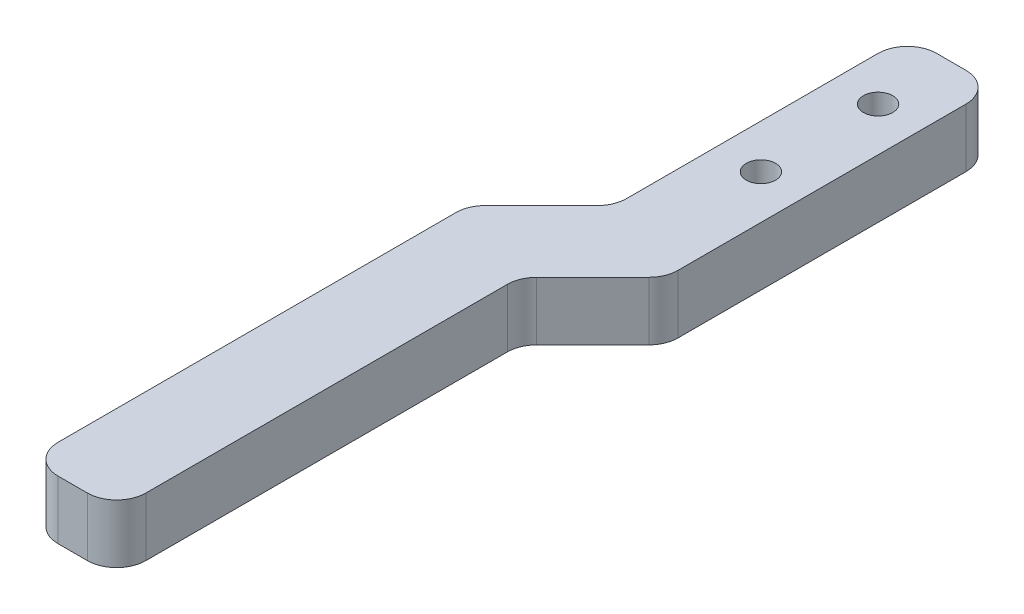
SolidWorks part; units mm, degrees
material "Thornel Mat VMA"
ref_plane "前视基准面" through (0, 0, 0) normal (0, 0, 1) x (1, 0, 0)
ref_plane "上视基准面" through (0, 0, 0) normal (0, 1, 0) x (1, 0, 0)
ref_plane "右视基准面" through (0, 0, 0) normal (1, 0, 0) x (0, 0, -1)
other "Configuration Table"
sketch "草图1" plane through (0, 0, 0) normal (0, 1, 0) x (1, 0, 0)
  line L0 (0, 0) -> (0, 40.389) construction
  line L1 (0, 0) -> (49.8304, 0) construction
  line L2 (0, 35) -> (25, 35) construction
  line L3 (25, 35) -> (25, 30) construction
  line L5 (25, 30) -> (15, 20) construction
  line L6 (25, -30) -> (15, -20) construction
  line L7 (25, 30) -> (25, 40)
  line L8 (25, -35) -> (25, -30) construction
  line L9 (0, -35) -> (25, -35) construction
  line L10 (0, 35) -> (0, -35) construction
  line L12 (31, 25.5147) -> (31, 37.5147)
  line L14 (25, 40) -> (30, 45)
  line L17 (31, 37.5147) -> (36, 42.5147)
  line L18 (30, 45) -> (30, 65)
  line L19 (30, 65) -> (36, 65)
  line L20 (36, 65) -> (36, 42.5147)
  line L21 (33, 65) -> (33, 39.979) construction
  line L22 (0, 0) -> (25, 0) construction
  line L23 (25, 0) -> (25, 30) construction
  line L24 (25, 30) -> (25, 10)
  line L25 (25, 10) -> (31, 10)
  line L26 (31, 10) -> (31, 25.5147)
  arc A0 (15, -20) -> (15, 20) centre (0, 0) ccw construction
  circle A4 centre (33, 60) radius 1
  circle A5 centre (33, 52) radius 1
  dimension "D3" = 50
  dimension "D11" = 0
  dimension "D12" = 20
  dimension "D13" = 2
  dimension "D14" = 2
  dimension "D15" = 8
  dimension "D16" = 5
  dimension "D17" = 6
  dimension "D1" = 5
  dimension "D2" = 25
  dimension "D4" = 35
  dimension "D5" = 45
  dimension "D6" = 6
  dimension "D7" = 135
  dimension "D8" = 10
  dimension "D9" = 5
  dimension "D10" = 6
  dimension "D18" = 25
  dimension "D19" = 12
extrude "凸台-拉伸1" add sketch "草图1" along normal blind 4
fillet "圆角1" radius 2 8 edges at (31, 2, -37.5147) (25, 2, -40) (30, 2, -45) (36, 2, -42.5147) (36, 2, -65) (30, 2, -65) (31, 2, -10) (25, 2, -10)
